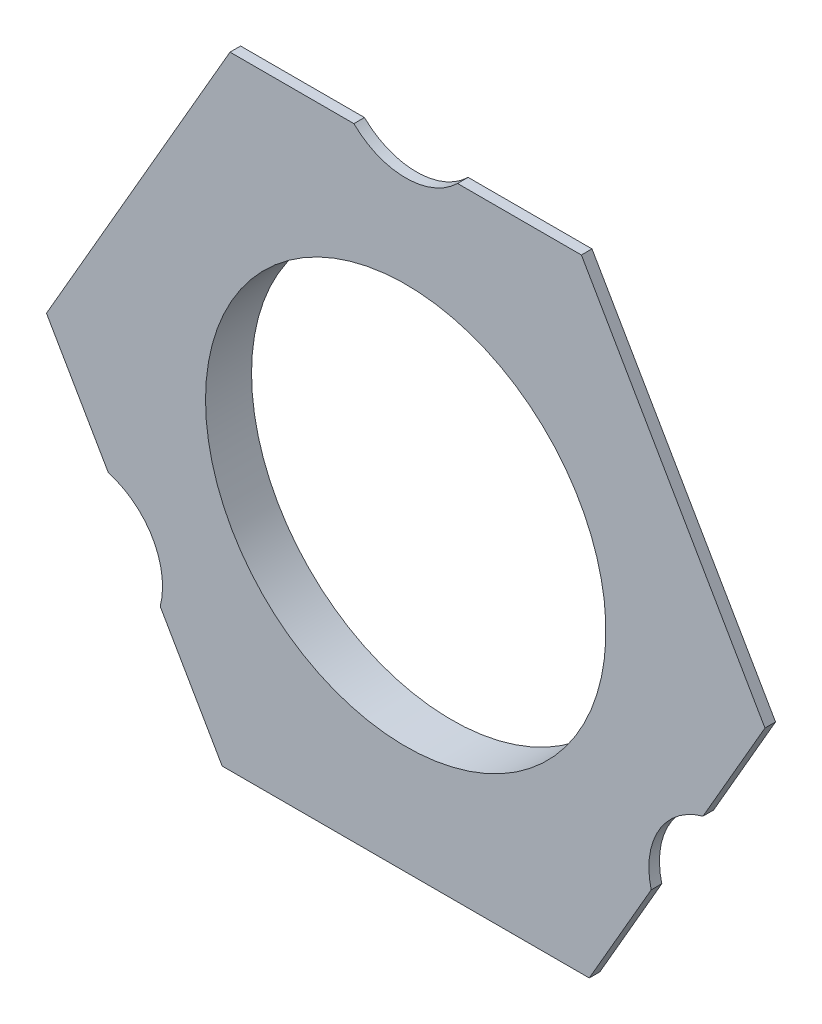
SolidWorks part; units mm, degrees
ref_plane "Front Plane" through (0, 0, 0) normal (0, 0, 1) x (1, 0, 0)
ref_plane "Top Plane" through (0, 0, 0) normal (0, 1, 0) x (1, 0, 0)
ref_plane "Right Plane" through (0, 0, 0) normal (1, 0, 0) x (0, 0, -1)
sketch "Sketch1" plane through (0, 0, 0) normal (0, 1, 0) x (1, 0, 0)
  line L0 (0, 73.9814) -> (0, -55.3241) construction
  line L1 (-91.4726, 0) -> (90.4361, 0) construction
  line L2 (37.85, 0) -> (37.85, -18.7)
  line L3 (37.85, -18.7) -> (44.5, -18.7)
  line L4 (44.5, -18.7) -> (44.5, -16.2)
  line L5 (44.5, -16.2) -> (43.5, -16.2)
  line L6 (43.5, -16.2) -> (43.5, -11.2)
  line L7 (43.5, -11.2) -> (44.5, -11.2)
  line L8 (44.5, -11.2) -> (44.5, -8.7)
  line L9 (44.5, -8.7) -> (55.25, -8.7)
  line L10 (55.25, -8.7) -> (55.25, -6.7)
  line L11 (55.25, -6.7) -> (39.85, -6.7)
  line L12 (39.85, -6.7) -> (39.85, 0)
  line L13 (39.85, 0) -> (37.85, 0)
  point P8 (39.85, -3.35)
  dimension "D1" = 55.25
  dimension "D2" = 39.85
  dimension "D3" = 44.5
  dimension "D4" = 6.7
  dimension "D5" = 2
  dimension "D6" = 2
  dimension "D7" = 10
  dimension "D8" = 5
  dimension "D9" = 2.5
  dimension "D10" = 1
  dimension "D11" = 44.5
revolve "Revolve1" add sketch "Sketch1" angle 360 about L0
chamfer "Chamfer1" distance 0.25 angle 45 4 edges at (-44.5, 0, 11.2) (-43.5, 0, 11.2) (-43.5, 0, 16.2) (-44.5, 0, 16.2)
sketch "Sketch2" plane through (0, 0, 8.7) normal (0, 0, 1) x (1, 0, 0)
  line L0 (0, 99.1772) -> (0, -96.216) construction
  line L1 (-93.7434, 0) -> (96.5768, 0) construction
  line L2 (-78.2888, 55.25) -> (80.948, 55.25) construction
  line L3 (9.798, 59.25) -> (33.218, 59.25)
  line L4 (-9.798, 59.25) -> (-33.218, 59.25)
  line L12 (46.413, -38.1103) -> (34.703, -58.3926)
  line L13 (56.211, -21.1397) -> (67.921, -0.8574)
  line L14 (85.89, -49.5886) -> (-83.3255, 48.108) construction
  line L15 (86.9923, 40.1751) -> (7.3739, -97.7281) construction
  line L16 (-56.211, -21.1397) -> (-67.921, -0.8574)
  line L17 (-46.413, -38.1103) -> (-34.703, -58.3926)
  line L18 (-85.89, -49.5886) -> (83.3255, 48.108) construction
  line L19 (-8.7035, -95.4251) -> (-88.3219, 42.4781) construction
  line L20 (-33.218, 59.25) -> (-67.921, -0.8574)
  line L21 (-34.703, -58.3926) -> (34.703, -58.3926)
  line L22 (67.921, -0.8574) -> (33.218, 59.25)
  arc A0 (-9.798, 59.25) -> (9.798, 59.25) centre (0, 69.25) ccw
  arc A3 (56.211, -21.1397) -> (46.413, -38.1103) centre (59.9723, -34.625) ccw
  circle A5 centre (0, 0) radius 44.5 construction
  circle A6 centre (0, 0) radius 44.5
  arc A7 (-46.413, -38.1103) -> (-56.211, -21.1397) centre (-59.9723, -34.625) ccw
  point P25 (0, 0)
  point P37 (0, 0)
  dimension "D2" = 28
  dimension "D5" = 3
  dimension "D1" = 55.25
  dimension "D3" = 4
  dimension "D4" = 23.42
extrude "Boss-Extrude1" add sketch "Sketch2" against normal blind 2
sketch "Sketch3" plane through (0, 0, 8.7) normal (0, 0, 1) x (1, 0, 0)
  line L0 (0, 80.6559) -> (0, -68.3074) construction
  line L1 (-103.6252, 0) -> (137.5272, 0) construction
  line L20 (-33.1025, 59.05) -> (-67.69, -0.8574)
  line L21 (-67.69, -0.8574) -> (-56.0784, -20.9693)
  line L22 (-46.1992, -38.0807) -> (-34.5876, -58.1926)
  line L23 (-34.5876, -58.1926) -> (34.5876, -58.1926)
  line L24 (34.5876, -58.1926) -> (46.1992, -38.0807)
  line L25 (56.0784, -20.9693) -> (67.69, -0.8574)
  line L26 (67.69, -0.8574) -> (33.1025, 59.05)
  line L27 (33.1025, 59.05) -> (9.8793, 59.05)
  line L28 (-9.8793, 59.05) -> (-33.1025, 59.05)
  line L29 (-33.1025, 59.05) -> (-67.69, -0.8574)
  line L30 (-67.69, -0.8574) -> (-56.0784, -20.9693)
  line L31 (-46.1992, -38.0807) -> (-34.5876, -58.1926)
  line L32 (-34.5876, -58.1926) -> (34.5876, -58.1926)
  line L33 (34.5876, -58.1926) -> (46.1992, -38.0807)
  line L34 (56.0784, -20.9693) -> (67.69, -0.8574)
  line L35 (67.69, -0.8574) -> (33.1025, 59.05)
  line L36 (33.1025, 59.05) -> (9.8793, 59.05)
  line L37 (-9.8793, 59.05) -> (-33.1025, 59.05)
  circle A4 centre (0, 0) radius 112.968
  arc A6 (-46.1992, -38.0807) -> (-56.0784, -20.9693) centre (-59.9723, -34.625) ccw
  arc A7 (56.0784, -20.9693) -> (46.1992, -38.0807) centre (59.9723, -34.625) ccw
  arc A8 (-9.8793, 59.05) -> (9.8793, 59.05) centre (0, 69.25) ccw
  arc A9 (-46.1992, -38.0807) -> (-56.0784, -20.9693) centre (-59.9723, -34.625) ccw
  arc A10 (56.0784, -20.9693) -> (46.1992, -38.0807) centre (59.9723, -34.625) ccw
  arc A11 (-9.8793, 59.05) -> (9.8793, 59.05) centre (0, 69.25) ccw
  dimension "D1" = 0.2
sketch "Sketch4" plane through (0, 0, 0) normal (0, 1, 0) x (1, 0, 0)
  line L0 (0, 30.4627) -> (0, -30.9668) construction
  line L1 (-70.8914, -8.7) -> (79.1888, -8.7) construction
  line L3 (-57.3536, -8.7) -> (58.3726, -8.7)
  line L4 (-57.3536, -8.7) -> (-57.3536, -27.0365)
  line L5 (-57.3536, -27.0365) -> (58.3726, -27.0365)
  line L6 (58.3726, -8.7) -> (58.3726, -27.0365)
extrude "Cut-Extrude3" cut sketch "Sketch4" against normal through all both and the other way through all
chamfer "Chamfer2" distance 0.25 angle 45 1 edges at (-39.85, 0, 0)
